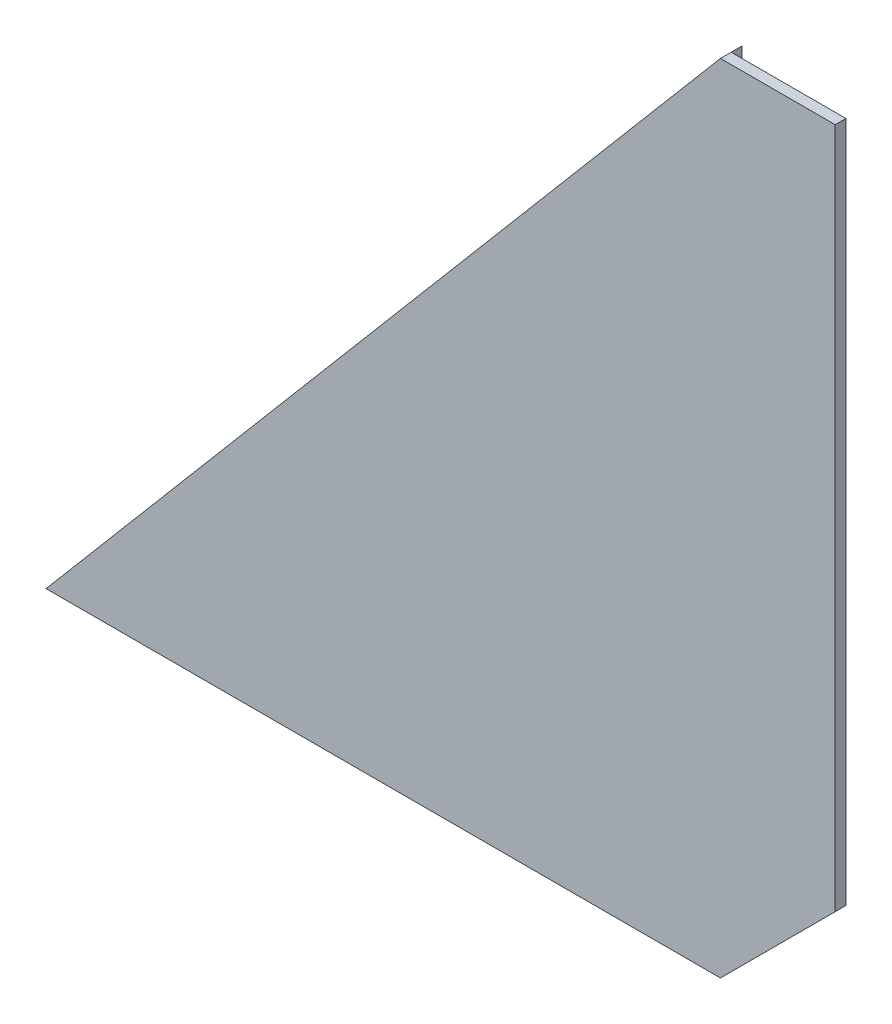
SolidWorks part; units mm, degrees
ref_plane "前基準面" through (0, 0, 0) normal (0, 0, 1) x (1, 0, 0)
ref_plane "上基準面" through (0, 0, 0) normal (0, 1, 0) x (1, 0, 0)
ref_plane "右基準面" through (0, 0, 0) normal (1, 0, 0) x (0, 0, -1)
ref_plane "平面1"
sketch "草圖1" plane through (0, 0, 0) normal (0, 0, 1) x (1, 0, 0)
  line L0 (-16, 0) -> (0, 16)
  line L1 (0, 16) -> (0, 111)
  line L2 (0, 111) -> (-16, 111)
  line L3 (-16, 111) -> (-16, 97.0735)
  line L4 (-16, 97.0735) -> (-98.2064, 0)
  line L5 (-98.2064, 0) -> (-16, 0)
  dimension "D1" = 16
  dimension "D2" = 16
  dimension "D3" = 95
  dimension "D4" = 16
extrude "擠出1" add sketch "草圖1" along normal blind 1.5
ref_plane "平面2" through (0, 0, 0) normal (0, 0, 1) x (1, 0, 0)
sketch "草圖2" plane through (0, 0, 0) normal (0, 0, 1) x (1, 0, 0)
  line L0 (-110, 0) -> (-98.2064, 0)
  line L1 (-98.2064, 0) -> (-16, 97.0735)
  line L2 (-16, 97.0735) -> (-16, 111)
  line L3 (-16, 111) -> (-110, 0)
  dimension "D1" = 16
  dimension "D2" = 16
  dimension "D3" = 94
  dimension "D4" = 95
  dimension "D5" = 16
  dimension "D6" = 9
extrude "擠出2" add sketch "草圖2" along normal blind 3
ref_plane "平面3" through (-44.2195, 22.2, 0) normal (0, 0, 1) x (1, 0, 0)
mirror "鏡射1" about plane through (-44.2195, 22.2, 0) normal (0, 0, 1) of bodies 102
delete or keep bodies "鏡射2" type delete bodies bodies 102
